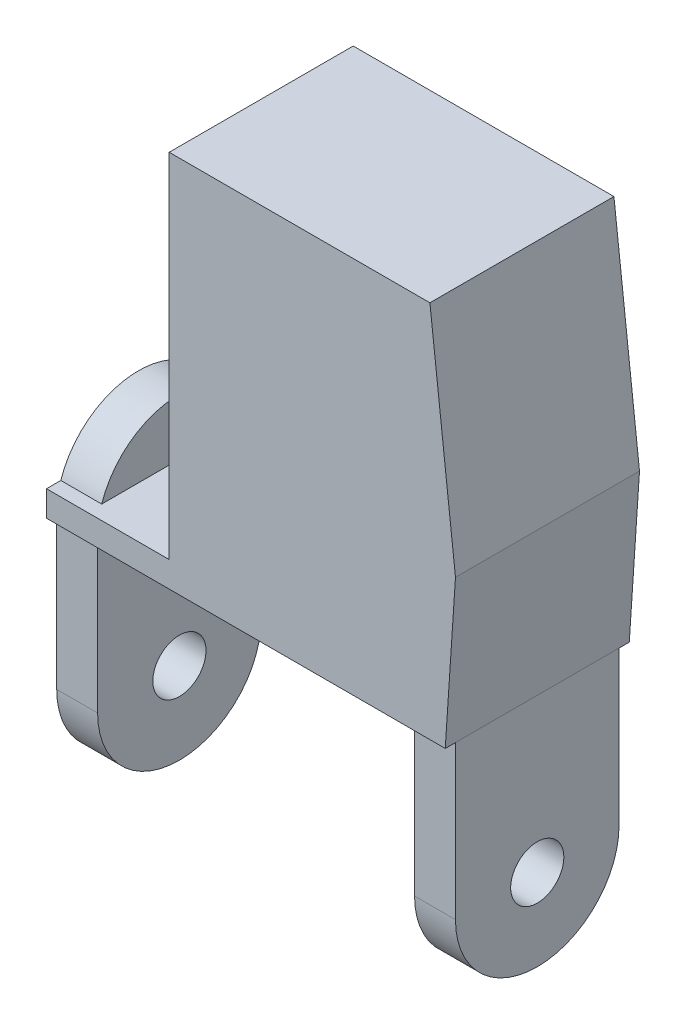
SolidWorks part; units mm, degrees
material "Nylon 101"
ref_plane "Alzado" through (0, 0, 0) normal (0, 0, 1) x (1, 0, 0)
ref_plane "Planta" through (0, 0, 0) normal (0, 1, 0) x (1, 0, 0)
ref_plane "Vista lateral" through (0, 0, 0) normal (1, 0, 0) x (0, 0, -1)
ref_plane "Plane2" through (0, 0, -9) normal (0, 0, 1) x (1, 0, 0)
sketch "Sketch1" plane through (0, 0, -9) normal (0, 0, 1) x (1, 0, 0)
  line L0 (-7.5, 52) -> (18, 52)
  line L1 (18, 52) -> (20.5, 30)
  line L2 (20.5, 30) -> (19.5, 15)
  line L3 (19.5, 15) -> (-19.5, 15)
  line L4 (-19.5, 15) -> (-19.5, 17.5)
  line L5 (-19.5, 17.5) -> (-7.5, 17.5)
  line L6 (-7.5, 17.5) -> (-7.5, 52)
extrude "Epifisis_distal" add sketch "Sketch1" along normal blind 18
ref_plane "Plane4" through (-19.5, 0, 0) normal (1, 0, 0) x (0, 0, -1)
sketch "Sketch2" plane through (-19.5, 0, 0) normal (1, 0, 0) x (0, 0, -1)
  line L0 (0, 15) -> (0, 0) construction
  line L1 (8, 15) -> (8, 0)
  line L2 (-8, 15) -> (-8, 0)
  arc A0 (8, 15) -> (-8, 15) centre (0, 15) ccw
  arc A1 (-8, 0) -> (8, 0) centre (0, 0) ccw
  point P3 (0, 7.5)
  point P8 (0, 0)
extrude "Oreja_medial" add sketch "Sketch2" along normal blind 4
ref_plane "Plane5" through (15.5, 0, 0) normal (1, 0, 0) x (0, 0, -1)
sketch "Sketch3" plane through (15.5, 0, 0) normal (1, 0, 0) x (0, 0, -1)
  line L0 (0, 15) -> (0, 0) construction
  line L1 (8, 15) -> (8, 0)
  line L2 (-8, 15) -> (-8, 0)
  arc A0 (8, 15) -> (-8, 15) centre (0, 15) ccw
  arc A1 (-8, 0) -> (8, 0) centre (0, 0) ccw
  point P3 (0, 7.5)
  point P8 (0, 0)
extrude "Oreja_lateral" add sketch "Sketch3" along normal blind 4
sketch "Sketch4" plane through (0, 0, 0) normal (1, 0, 0) x (0, 0, -1)
  circle A0 centre (0, 0) radius 2.6
extrude "Agujero_eje_muneca" cut sketch "Sketch4" against normal mid plane 2000
